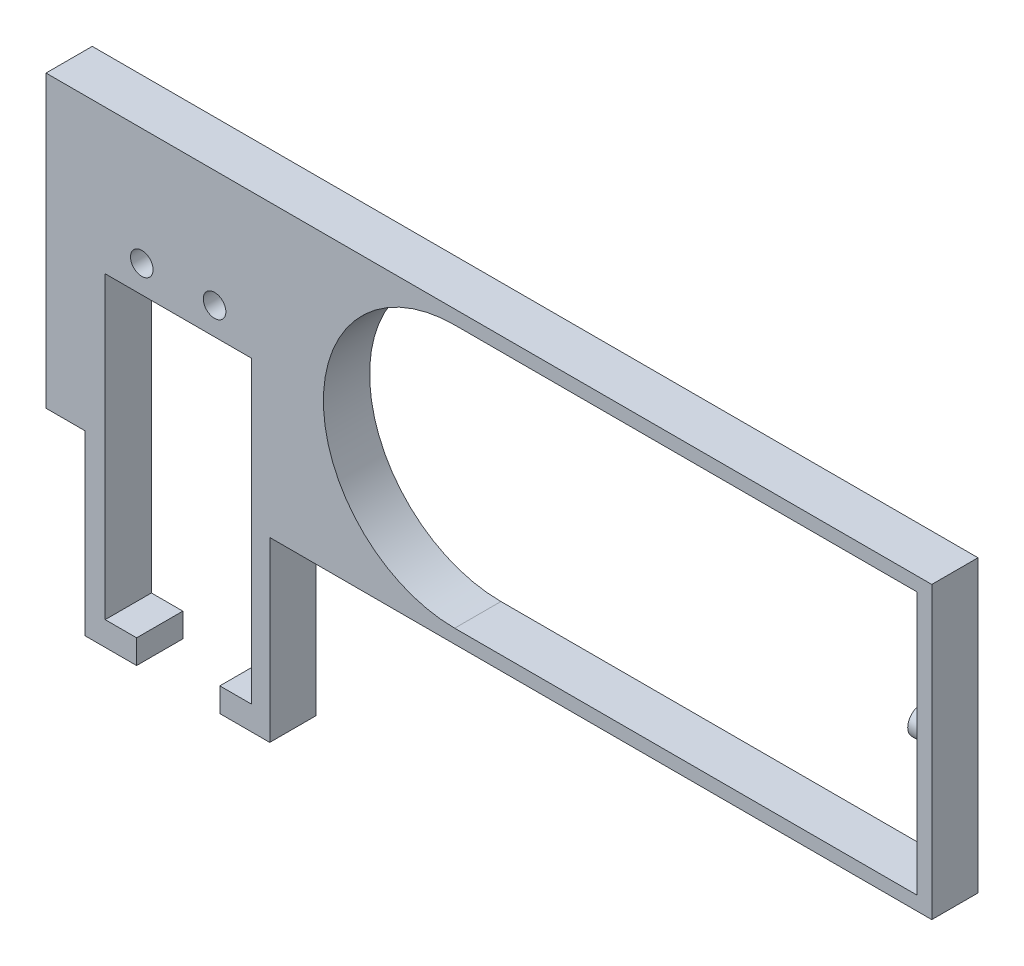
SolidWorks part; units mm, degrees
other "first"
other "second" parameters "D1"=6.35
ref_plane "Front Plane" through (0, 0, 0) normal (0, 0, 1) x (1, 0, 0)
ref_plane "Top Plane" through (0, 0, 0) normal (0, 1, 0) x (1, 0, 0)
ref_plane "Right Plane" through (0, 0, 0) normal (1, 0, 0) x (0, 0, -1)
sketch "Sketch1" plane through (0, 0, 0) normal (0, 0, 1) x (1, 0, 0)
  circle A0 centre (0, 0) radius 19.939
  dimension "D1" = 39.878
extrude "circle extrude" add sketch "Sketch1" along normal blind 6.35
sketch "Sketch3" plane through (0, 0, 0) normal (1, 0, 0) x (0, 0, -1)
  line L0 (0, 35.3441) -> (0, -35.3441) construction
  line L1 (-6.35, 19.939) -> (0, 19.939)
  line L2 (-6.35, 19.939) -> (-6.35, -19.939)
  line L3 (-6.35, -19.939) -> (0, -19.939)
  line L4 (0, 19.939) -> (0, -19.939)
  line L5 (-6.35, -19.939) -> (0, -19.939) construction
extrude "rectangle extrude" add sketch "Sketch3" along normal blind 127
sketch "Sketch2" plane through (0, 0, 6.35) normal (0, 0, 1) x (1, 0, 0)
  circle A0 centre (0, 0) radius 18.034
  dimension "D1" = 36.068
extrude "circle cut" cut sketch "Sketch2" against normal through all
sketch "Sketch6" plane through (0, 0, 6.35) normal (0, 0, 1) x (1, 0, 0)
  line L1 (125.095, -18.034) -> (125.095, 18.034)
  line L3 (0, -18.034) -> (0, 18.034)
  line L4 (0, -18.034) -> (125.095, -18.034)
  line L5 (127, -19.939) -> (0, -19.939) construction
  line L6 (0, 18.034) -> (125.095, 18.034)
  line L8 (127, 19.939) -> (127, -19.939) construction
  arc A0 (0, 19.939) -> (0, -19.939) centre (0, 0) ccw construction
  circle A1 centre (0, 0) radius 18.034 construction
  point P5 (125.095, 0)
  point P12 (0, 0)
  point P17 (-19.939, 0)
  dimension "D1" = 1.905
  dimension "D2" = 1.905
  dimension "D3" = 19.939
extrude "rectangle cut" cut sketch "Sketch6" against normal through all
sketch "Sketch7" plane through (0, 0, 6.35) normal (0, 0, 1) x (1, 0, 0)
  line L1 (63.5, 18.034) -> (125.095, 18.034)
  line L2 (125.095, -18.034) -> (125.095, 18.034) construction
  line L3 (125.095, 18.034) -> (125.095, -18.034)
  line L4 (125.095, -18.034) -> (63.5, -18.034)
  line L5 (63.5, 18.034) -> (63.5, -18.034)
  line L6 (125.095, 18.034) -> (0, 18.034) construction
  dimension "D2" = 63.5
extrude "end shape" add sketch "Sketch7" against normal blind 6.35
sketch "Sketch8" plane through (63.5, 0, 0) normal (-1, 0, 0) x (0, 0, 1)
  line L1 (0, 19.939) -> (6.35, 19.939) construction
  line L2 (3.175, 19.939) -> (3.175, 0) construction
  circle A0 centre (3.175, 0) radius 1.905
  dimension "D1" = 3.81
extrude "for spring extrude" add sketch "Sketch8" along normal blind 2.54
pattern_linear "mirrored pattern" count 2 spacing 254 along (1, 0, 0) of bodies 109
sketch "Sketch10" plane through (127, 0, 0) normal (1, 0, 0) x (0, 0, -1)
  line L1 (-6.35, 19.939) -> (0, 19.939)
  line L2 (-6.35, 19.939) -> (-6.35, -19.939)
  line L3 (-6.35, -19.939) -> (0, -19.939)
  line L4 (0, 19.939) -> (0, -19.939)
extrude "middle connector" add sketch "Sketch10" along normal up to next
sketch "Sketch11" plane through (381, 0, 0) normal (1, 0, 0) x (0, 0, -1)
  line L1 (-6.35, 19.939) -> (0, 19.939)
  line L2 (-6.35, 19.939) -> (-6.35, -19.939)
  line L3 (-6.35, -19.939) -> (0, -19.939)
  line L4 (0, 19.939) -> (0, -19.939)
extrude "end cut" cut sketch "Sketch11" against normal blind 55.88
sketch "Sketch12" plane through (0, 0, 6.35) normal (0, 0, 1) x (1, 0, 0)
  line L0 (325.12, -19.939) -> (0, -19.939) construction
  line L1 (226.06, -41.021) -> (205.994, -41.021)
  line L2 (226.06, -41.021) -> (226.06, 0.127)
  line L3 (226.06, 0.127) -> (205.994, 0.127)
  line L4 (205.994, -41.021) -> (205.994, 0.127)
  line L5 (325.12, 19.939) -> (325.12, -19.939) construction
  dimension "D1" = 99.06
  dimension "D2" = 20.066
  dimension "D3" = 41.148
  dimension "D4" = 20.066
sketch "Sketch13" plane through (0, 0, 6.35) normal (0, 0, 1) x (1, 0, 0)
  line L0 (325.12, -19.939) -> (0, -19.939) construction
  line L1 (203.2, 0.127) -> (228.6, 0.127)
  line L2 (203.2, 0.127) -> (203.2, -44.323)
  line L3 (203.2, -44.323) -> (228.6, -44.323)
  line L4 (228.6, 0.127) -> (228.6, -44.323)
  line L5 (325.12, 19.939) -> (325.12, -19.939) construction
  point P4 (215.9, 0.127)
  dimension "D1" = 25.4
  dimension "D2" = 44.45
  dimension "D3" = 96.52
  dimension "D4" = 20.066
extrude "Boss-Extrude1" add sketch "Sketch13" against normal up to surface (6.35 mm away) up to face at (281.2415, 0, 0)
extrude "Cut-Extrude1" cut sketch "Sketch12" against normal through all
pattern_linear "LPattern1" count 2 spacing 107.188 along (-1, 0, 0) of "Boss-Extrude1", "Cut-Extrude1"
sketch "Sketch14" plane through (0, 0, 0) normal (0, 0, -1) x (-1, 0, 0)
  line L0 (-325.12, 19.939) -> (0, 19.939) construction
  circle A0 centre (-103.96, 3.88) radius 1.55
  circle A1 centre (-113.96, 3.88) radius 1.55
  circle A2 centre (-211.021, 3.88) radius 1.55
  circle A3 centre (-221.021, 3.88) radius 1.55
  dimension "D3" = 3.1
  dimension "D1" = 16.059
  dimension "D2" = 10
  dimension "D4" = 10
  dimension "D5" = 16.059
extrude "Cut-Extrude2" cut sketch "Sketch14" against normal through all
sketch "Sketch15" plane through (0, 0, 6.35) normal (0, 0, 1) x (1, 0, 0)
  line L1 (197.866, 38.9223) -> (-28.4084, 38.9223)
  line L2 (197.866, 38.9223) -> (197.866, -70.7865)
  line L3 (197.866, -70.7865) -> (-28.4084, -70.7865)
  line L4 (-28.4084, 38.9223) -> (-28.4084, -70.7865)
  arc A0 (254, 18.034) -> (254, -18.034) centre (254, 0) ccw construction
  point P7 (235.966, 0)
  dimension "D1" = 38.1
extrude "Cut-Extrude3" [suppressed] cut sketch "Sketch15" against normal through all
sketch "Sketch16" plane through (0, 0, 6.35) normal (0, 0, 1) x (1, 0, 0)
  line L0 (216.027, -41.021) -> (216.027, -44.3254) construction
  line L4 (205.994, -41.021) -> (226.06, -41.021) construction
  line L5 (203.2, -44.323) -> (228.6, -44.323) construction
  line L6 (210.312, -41.021) -> (221.742, -41.021)
  line L7 (210.312, -41.021) -> (210.312, -44.323)
  line L8 (210.312, -44.323) -> (221.742, -44.323)
  line L9 (221.742, -41.021) -> (221.742, -44.323)
  point P10 (216.027, -41.021)
  dimension "D1" = 11.43
extrude "Cut-Extrude4" cut sketch "Sketch16" against normal through all
sketch "Sketch17" plane through (0, 0, 6.35) normal (0, 0, 1) x (1, 0, 0)
  line L0 (325.12, 19.939) -> (0, 19.939) construction
  line L1 (197.866, 33.0005) -> (-46.7971, 33.0005)
  line L2 (197.866, 33.0005) -> (197.866, -52.3978)
  line L3 (197.866, -52.3978) -> (-46.7971, -52.3978)
  line L4 (-46.7971, 33.0005) -> (-46.7971, -52.3978)
  line L5 (317.5, 18.034) -> (317.5, -18.034) construction
  line L6 (319.532, 19.939) -> (325.12, 19.939)
  line L7 (319.532, 19.939) -> (319.532, -19.939)
  line L8 (319.532, -19.939) -> (325.12, -19.939)
  line L9 (325.12, 19.939) -> (325.12, -19.939)
  arc A0 (254, 18.034) -> (254, -18.034) centre (254, 0) ccw construction
  point P7 (235.966, 0)
  dimension "D1" = 38.1
  dimension "D3" = 2.032
extrude "Cut-Extrude5" cut sketch "Sketch17" against normal through all
equation "\"wall_thickness\"= 0.125in"
equation "\"base_thickness\"= 0.25in"
equation "\"D1@circle extrude\"=\"wall_thickness\""
